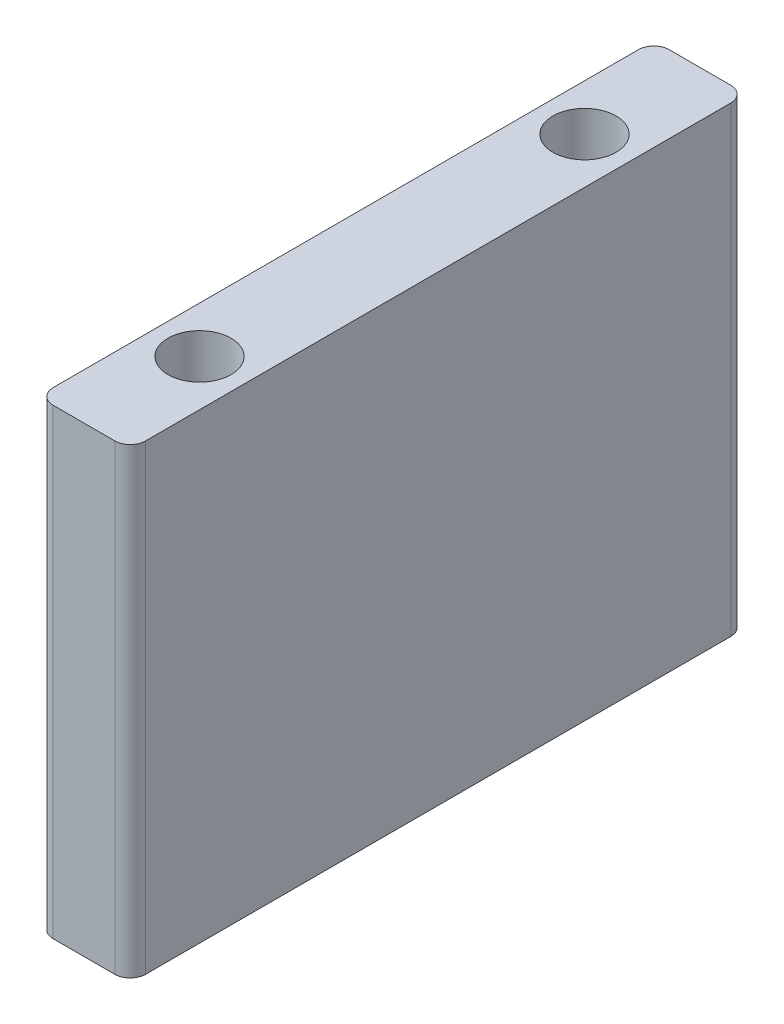
SolidWorks part; units mm, degrees
ref_plane "前视基准面" through (0, 0, 0) normal (0, 0, 1) x (1, 0, 0)
ref_plane "上视基准面" through (0, 0, 0) normal (0, 1, 0) x (1, 0, 0)
ref_plane "右视基准面" through (0, 0, 0) normal (1, 0, 0) x (0, 0, -1)
sketch "草图1" plane through (0, 0, 0) normal (0, 1, 0) x (1, 0, 0)
  line L0 (0, 20) -> (0, -20) construction
  line L1 (-2, 20) -> (2, 20)
  line L2 (-3, 19) -> (-3, -19)
  line L3 (-2, -20) -> (2, -20)
  line L4 (3, 19) -> (3, -19)
  line L5 (-3, 20) -> (3, -20) construction
  line L6 (-3, -20) -> (3, 20) construction
  line L7 (0, 0) -> (3, 0) construction
  circle A0 centre (0, 12.5) radius 2.05
  circle A1 centre (0, -12.5) radius 2.05
  arc A2 (2, -20) -> (3, -19) centre (2, -19) ccw
  arc A3 (-3, -19) -> (-2, -20) centre (-2, -19) ccw
  arc A4 (2, 20) -> (3, 19) centre (2, 19) cw
  arc A5 (-2, 20) -> (-3, 19) centre (-2, 19) ccw
  point P0 (0, 0)
  dimension "D2" = 4.1
  dimension "D4" = 1
  dimension "D1" = 40
  dimension "D3" = 6
  dimension "D5" = 25
extrude "凸台-拉伸1" add sketch "草图1" along normal blind 30
